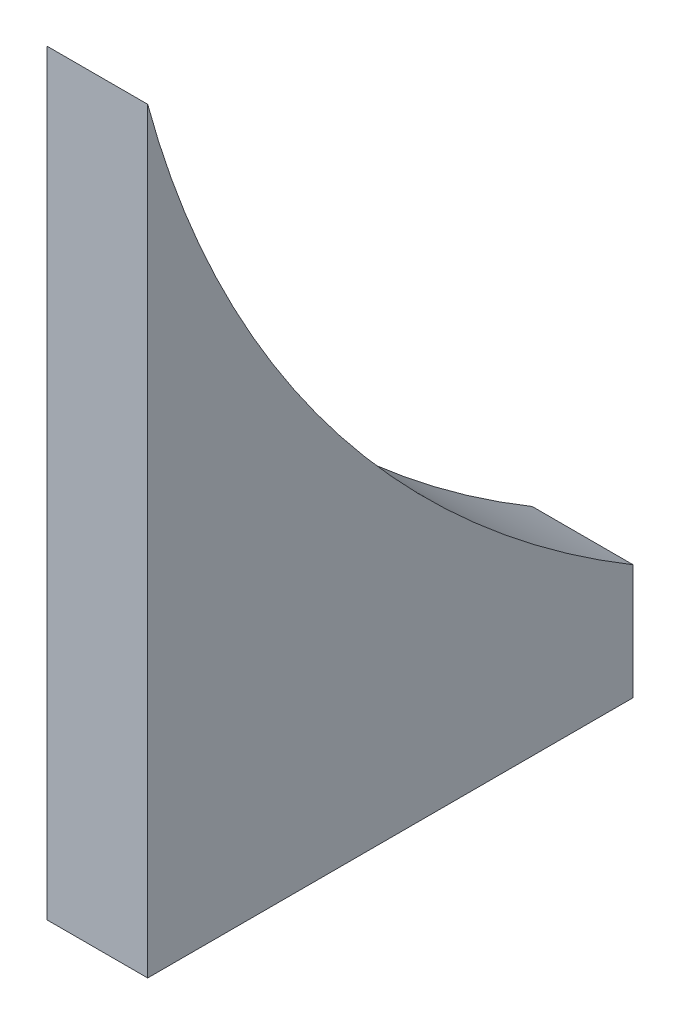
SolidWorks part; units mm, degrees
ref_plane "Front Plane" through (0, 0, 0) normal (0, 0, 1) x (1, 0, 0)
ref_plane "Top Plane" through (0, 0, 0) normal (0, 1, 0) x (1, 0, 0)
ref_plane "Right Plane" through (0, 0, 0) normal (1, 0, 0) x (0, 0, -1)
sketch "Sketch1" plane through (0, 0, 0) normal (1, 0, 0) x (0, 0, -1)
  line L0 (-11.8671, 22.332) -> (-11.8671, -7.668)
  line L1 (-11.8671, -7.668) -> (18.1329, -7.668)
  arc A0 (-11.8671, 22.332) -> (18.1329, -7.668) centre (29.2351, 33.4343) ccw
  dimension "D1" = 30
  dimension "D2" = 30
extrude "Boss-Extrude1" add sketch "Sketch1" along normal blind 4
sketch "Sketch2" plane through (4, 0, 0) normal (1, 0, 0) x (0, 0, -1)
  line L0 (-11.8671, 22.332) -> (-11.8671, -7.668) construction
  line L1 (18.1329, -7.668) -> (7.3829, -7.668)
  line L2 (18.1329, -7.668) -> (18.1329, 12.6592)
  line L3 (18.1329, 12.6592) -> (7.3829, 12.6592)
  line L4 (7.3829, -7.668) -> (7.3829, 12.6592)
  dimension "D1" = 19.25
extrude "Cut-Extrude1" cut sketch "Sketch2" against normal blind 4
